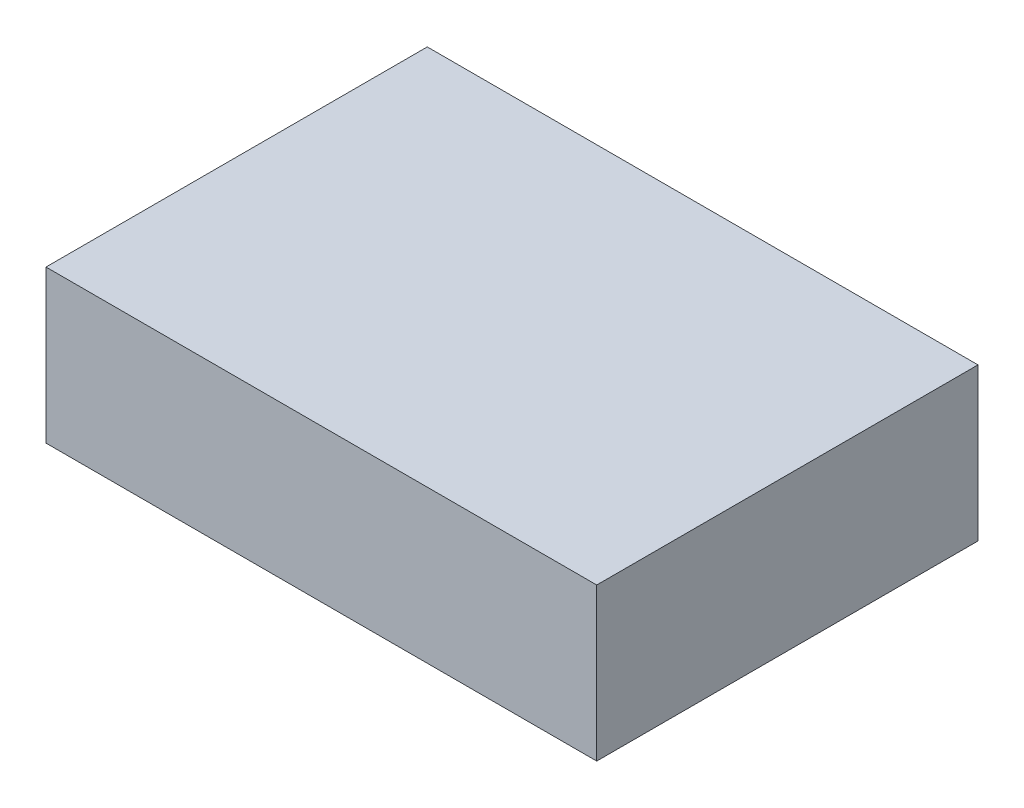
SolidWorks part; units mm, degrees
ref_plane "Front Plane" through (0, 0, 0) normal (0, 0, 1) x (1, 0, 0)
ref_plane "Top Plane" through (0, 0, 0) normal (0, 1, 0) x (1, 0, 0)
ref_plane "Right Plane" through (0, 0, 0) normal (1, 0, 0) x (0, 0, -1)
sketch "Sketch1" plane through (0, 0, 0) normal (0, 1, 0) x (1, 0, 0)
  line L1 (-16.51, -11.43) -> (16.51, -11.43)
  line L2 (-16.51, -11.43) -> (-16.51, 11.43)
  line L3 (-16.51, 11.43) -> (16.51, 11.43)
  line L4 (16.51, -11.43) -> (16.51, 11.43)
  line L5 (-16.51, -11.43) -> (16.51, 11.43) construction
  line L6 (-16.51, 11.43) -> (16.51, -11.43) construction
  point P0 (0, 0)
  dimension "D1" = 33.02
  dimension "D2" = 22.86
extrude "Boss-Extrude1" add sketch "Sketch1" along normal blind 9.144
